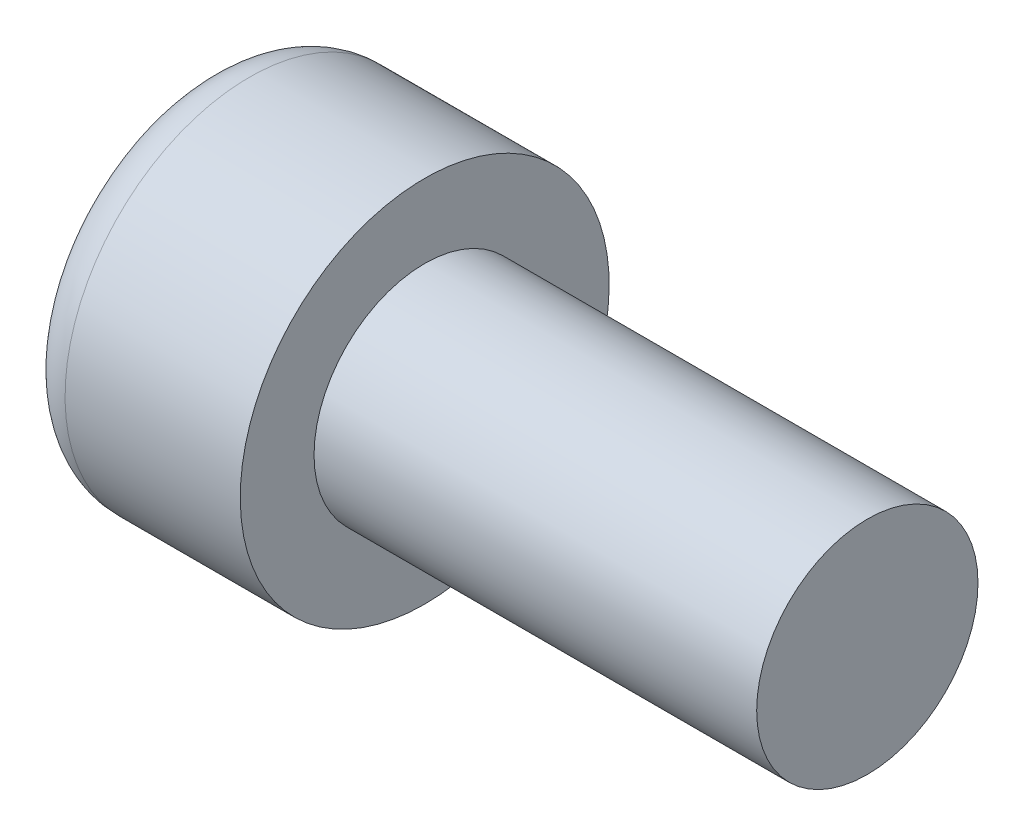
SolidWorks part; units mm, degrees
material "Plain Carbon Steel"
ref_plane "Front Plane" through (0, 0, 0) normal (0, 0, 1) x (1, 0, 0)
ref_plane "Top Plane" through (0, 0, 0) normal (0, 1, 0) x (1, 0, 0)
ref_plane "Right Plane" through (0, 0, 0) normal (1, 0, 0) x (0, 0, -1)
sketch "Sketch1" plane through (0, 0, 0) normal (0, 0, 1) x (1, 0, 0)
  line L0 (0, 0) -> (0, 3.75)
  line L1 (1.25, 5) -> (6, 5)
  line L2 (6, 5) -> (6, 3)
  line L3 (6, 3) -> (18, 3)
  line L4 (18, 3) -> (18, 0)
  line L5 (18, 0) -> (0, 0) construction
  line L6 (1.25, 3.75) -> (1.25, 2.5) construction
  line L7 (1.25, 2.5) -> (1.25, 1.25) construction
  line L8 (1.25, 1.25) -> (1.25, 0) construction
  line L9 (1.25, 5) -> (1.25, 3.75) construction
  line L10 (0, 0) -> (18, 0)
  arc A0 (0, 3.75) -> (1.25, 5) centre (1.25, 3.75) cw
  dimension "D1" = 6
  dimension "D2" = 10
  dimension "D3" = 6
  dimension "D4" = 12
revolve "Revolve1" add sketch "Sketch1" angle 360 about L10
sketch "Sketch2" plane through (0, 0, 0) normal (-1, 0, 0) x (0, 0, 1)
  line L1 (0, 2.8868) -> (-2.5, 1.4434)
  line L2 (-2.5, 1.4434) -> (-2.5, -1.4434)
  line L3 (-2.5, -1.4434) -> (0, -2.8868)
  line L4 (0, -2.8868) -> (2.5, -1.4434)
  line L5 (2.5, -1.4434) -> (2.5, 1.4434)
  line L6 (2.5, 1.4434) -> (0, 2.8868)
  circle A0 centre (0, 0) radius 2.5 construction
  dimension "D1" = 5
extrude "Cut-Extrude1" cut sketch "Sketch2" against normal blind 3.5
